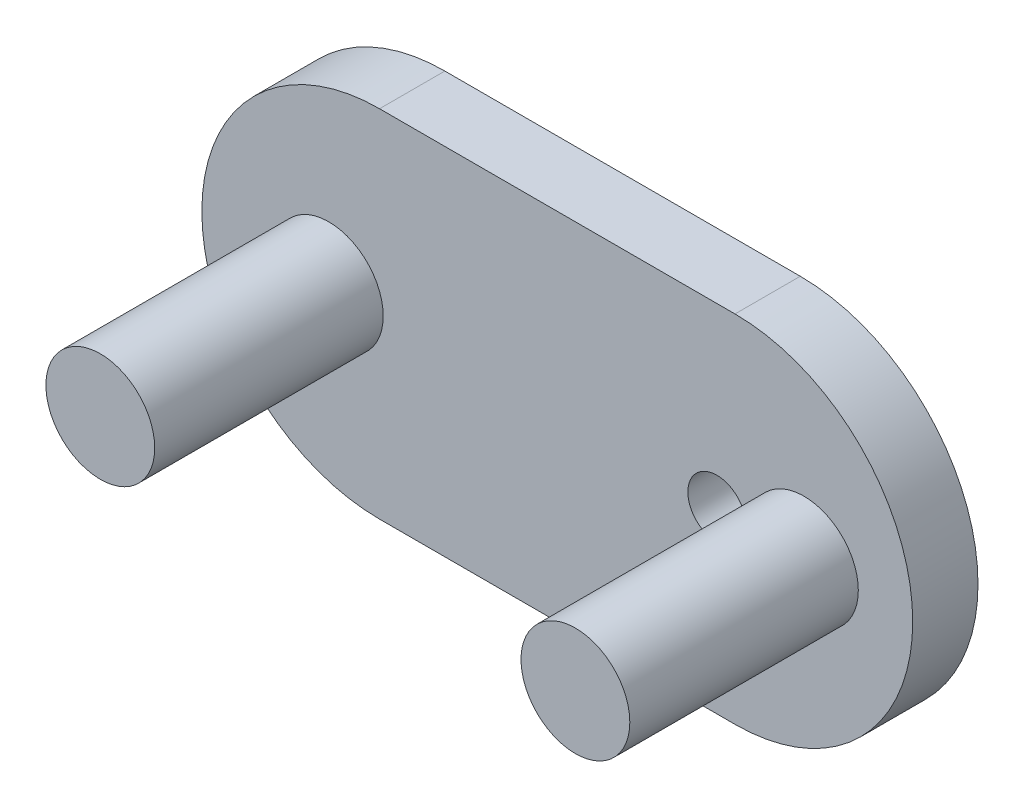
SolidWorks part; units mm, degrees
ref_plane "Piano frontale" through (0, 0, 0) normal (0, 0, 1) x (1, 0, 0)
ref_plane "Piano superiore" through (0, 0, 0) normal (0, 1, 0) x (1, 0, 0)
ref_plane "Piano destro" through (0, 0, 0) normal (1, 0, 0) x (0, 0, -1)
sketch "Schizzo1" plane through (0, 0, 0) normal (0, 0, 1) x (1, 0, 0)
  line L0 (-4.9, 0) -> (4.9, 0) construction
  line L1 (-4.9, 4.9) -> (4.9, 4.9)
  line L2 (4.9, -4.9) -> (-4.9, -4.9)
  line L3 (9.8, 0) -> (4.4, 0) construction
  arc A0 (-4.9, 4.9) -> (-4.9, -4.9) centre (-4.9, 0) ccw
  arc A1 (4.9, -4.9) -> (4.9, 4.9) centre (4.9, 0) ccw
  circle A2 centre (4.4, 0) radius 0.8
  dimension "D1" = 9.8
  dimension "D4" = 1.6
  dimension "D2" = 9.8
  dimension "D3" = 5.4
extrude "Estrusione-Estrusione1" add sketch "Schizzo1" along normal blind 1.8
sketch "Schizzo2" plane through (0, 0, 1.8) normal (0, 0, 1) x (1, 0, 0)
  line L0 (-9.8, 0) -> (-6.3, 0) construction
  arc A0 (-4.9, 4.9) -> (-4.9, -4.9) centre (-4.9, 0) ccw construction
  circle A1 centre (-6.3, 0) radius 1.5
  dimension "D2" = 3
  dimension "D1" = 3.5
extrude "Estrusione-Estrusione2" add sketch "Schizzo2" along normal blind 6.3
sketch "Schizzo3" plane through (0, 0, 1.8) normal (0, 0, 1) x (1, 0, 0)
  line L0 (9.8, 0) -> (6.8, 0) construction
  arc A0 (4.9, -4.9) -> (4.9, 4.9) centre (4.9, 0) ccw construction
  circle A1 centre (6.8, 0) radius 1.5
  dimension "D2" = 3
  dimension "D1" = 3
extrude "Estrusione-Estrusione3" add sketch "Schizzo3" along normal up to surface (6.3 mm away) up to face at (-4.8, 0, 8.1)
ref_plane "Piano1" through (0, 0, -61.2) normal (0, 0, 1) x (1, 0, 0)
sketch "Schizzo4" plane through (0, 0, -61.2) normal (0, 0, 1) x (1, 0, 0)
  line L0 (-9.8, 0) -> (43.2, 0) construction
  arc A0 (-4.9, 4.9) -> (-4.9, -4.9) centre (-4.9, 0) ccw construction
  dimension "D1" = 53
